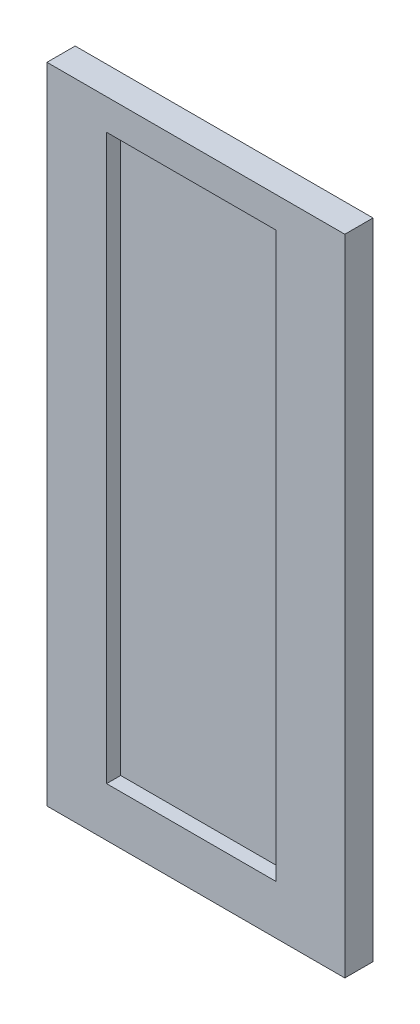
SolidWorks part; units mm, degrees
ref_plane "前视基准面" through (0, 0, 0) normal (0, 0, 1) x (1, 0, 0)
ref_plane "上视基准面" through (0, 0, 0) normal (0, 1, 0) x (1, 0, 0)
ref_plane "右视基准面" through (0, 0, 0) normal (1, 0, 0) x (0, 0, -1)
sketch "草图1" plane through (0, 0, 0) normal (0, 0, 1) x (1, 0, 0)
  line L0 (-10.5676, 5.4594) -> (42.2322, 5.4594)
  line L1 (42.2322, 5.4594) -> (42.2322, -108.7225)
  line L2 (42.2322, -108.7225) -> (-10.5676, -108.7225)
  line L3 (-10.5676, -108.7225) -> (-10.5676, 5.4594)
extrude "凸台-拉伸1" add sketch "草图1" against normal blind 5
sketch "草图3" plane through (0, 0, 0) normal (0, 0, 1) x (1, 0, 0)
  line L0 (0, 0) -> (30, 0)
  line L1 (30, 0) -> (30, -100)
  line L2 (30, -100) -> (0, -100)
  line L3 (0, -100) -> (0, 0)
extrude "切除-拉伸2" cut sketch "草图3" against normal blind 2.5
